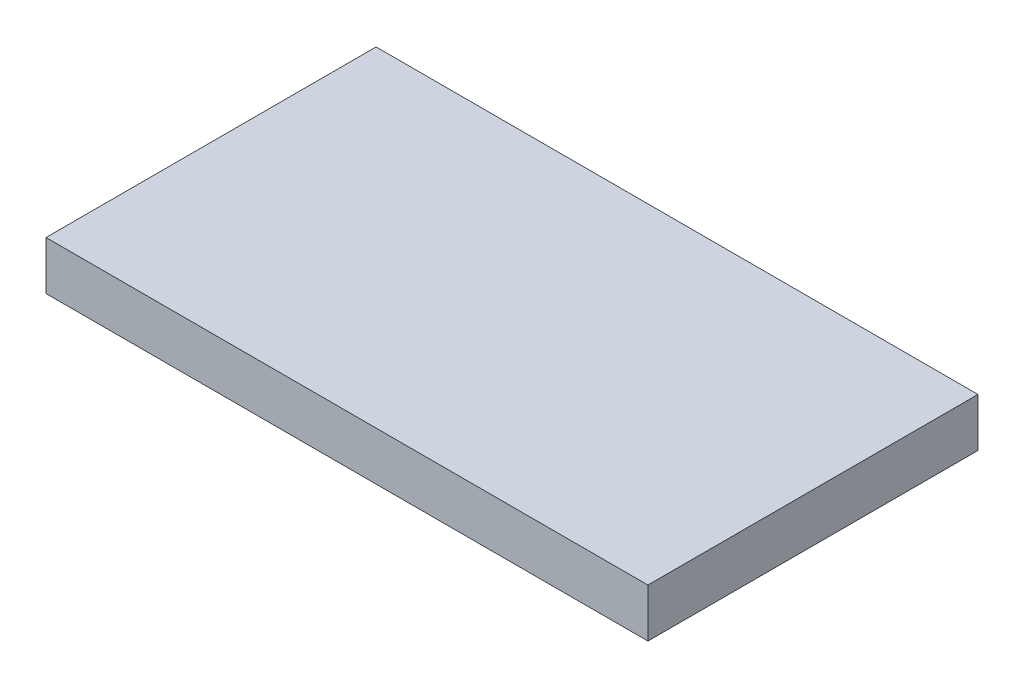
SolidWorks part; units mm, degrees
ref_plane "Front Plane" through (0, 0, 0) normal (0, 0, 1) x (1, 0, 0)
ref_plane "Top Plane" through (0, 0, 0) normal (0, 1, 0) x (1, 0, 0)
ref_plane "Right Plane" through (0, 0, 0) normal (1, 0, 0) x (0, 0, -1)
sketch "Sketch1" plane through (0, 0, 0) normal (0, 1, 0) x (1, 0, 0)
  line L1 (0, 0) -> (62, 0)
  line L2 (0, 0) -> (0, 34)
  line L3 (0, 34) -> (62, 34)
  line L4 (62, 0) -> (62, 34)
  dimension "D1" = 62
  dimension "D2" = 34
extrude "Boss-Extrude1" add sketch "Sketch1" along normal blind 5
